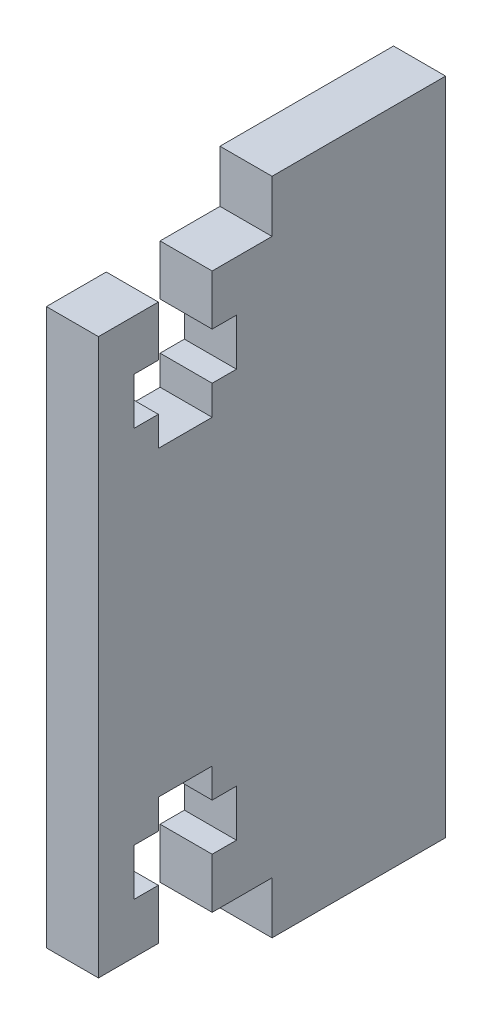
SolidWorks part; units mm, degrees
ref_plane "Front Plane" through (0, 0, 0) normal (0, 0, 1) x (1, 0, 0)
ref_plane "Top Plane" through (0, 0, 0) normal (0, 1, 0) x (1, 0, 0)
ref_plane "Right Plane" through (0, 0, 0) normal (1, 0, 0) x (0, 0, -1)
sketch "Sketch1" plane through (0, 0, 0) normal (1, 0, 0) x (0, 0, -1)
  line L1 (0, 0) -> (20, 0)
  line L2 (0, 0) -> (0, 38)
  line L3 (0, 38) -> (20, 38)
  line L4 (20, 0) -> (20, 38)
  dimension "D1" = 38
  dimension "D2" = 20
extrude "Boss-Extrude1" add sketch "Sketch1" along normal blind 3
sketch "Sketch2" plane through (3, 0, 0) normal (1, 0, 0) x (0, 0, -1)
  line L1 (0, 38) -> (10, 38)
  line L2 (0, 38) -> (0, 35)
  line L3 (0, 35) -> (10, 35)
  line L4 (10, 38) -> (10, 35)
  line L5 (0, 0) -> (10, 0)
  line L6 (0, 0) -> (0, 3)
  line L7 (0, 3) -> (10, 3)
  line L8 (10, 0) -> (10, 3)
  dimension "D1" = 10
  dimension "D2" = 10
  dimension "D3" = 3
  dimension "D4" = 3
extrude "Cut-Extrude1" cut sketch "Sketch2" against normal blind 3
sketch "Sketch3" plane through (3, 0, 0) normal (1, 0, 0) x (0, 0, -1)
  line L0 (3.45, 3) -> (3.45, 5.9)
  line L1 (3.45, 5.9) -> (2.05, 5.9)
  line L2 (2.05, 5.9) -> (2.05, 8.6)
  line L3 (2.05, 8.6) -> (3.45, 8.6)
  line L4 (3.45, 8.6) -> (3.45, 10.3)
  line L5 (3.45, 10.3) -> (6.55, 10.3)
  line L6 (6.55, 10.3) -> (6.55, 8.6)
  line L7 (6.55, 8.6) -> (7.95, 8.6)
  line L8 (7.95, 8.6) -> (7.95, 5.9)
  line L9 (7.95, 5.9) -> (6.55, 5.9)
  line L10 (6.55, 5.9) -> (6.55, 3)
  line L11 (6.55, 3) -> (3.45, 3)
  line L12 (10, 3) -> (0, 3) construction
  line L13 (0, 35) -> (0, 3) construction
  line L27 (0, 35) -> (10, 35) construction
  line B0 (6.55, 35) -> (6.55, 32.1)
  line B1 (6.55, 32.1) -> (7.95, 32.1)
  line B2 (7.95, 32.1) -> (7.95, 29.4)
  line B3 (7.95, 29.4) -> (6.55, 29.4)
  line B4 (6.55, 29.4) -> (6.55, 27.7)
  line B5 (6.55, 27.7) -> (3.45, 27.7)
  line B6 (3.45, 27.7) -> (3.45, 29.4)
  line B7 (3.45, 29.4) -> (2.05, 29.4)
  line B8 (2.05, 29.4) -> (2.05, 32.1)
  line B9 (2.05, 32.1) -> (3.45, 32.1)
  line B10 (3.45, 32.1) -> (3.45, 35)
  line B11 (3.45, 35) -> (6.55, 35)
  dimension "D1" = 1.7
  dimension "D2" = 2.7
  dimension "D3" = 2.9
  dimension "D4" = 3.1
  dimension "D5" = 1.4
  dimension "D6" = 0
  dimension "D7" = 3.45
  dimension "D8" = 0
  dimension "D9" = 3.45
sketch_block_instance "Block1-1"
sketch_block "Block1" parameters "D1"=3.1, "D2"=1.4, "D3"=1.7, "D4"=2.7, "D5"=2.9
extrude "Cut-Extrude2" cut sketch "Sketch3" against normal blind 3
